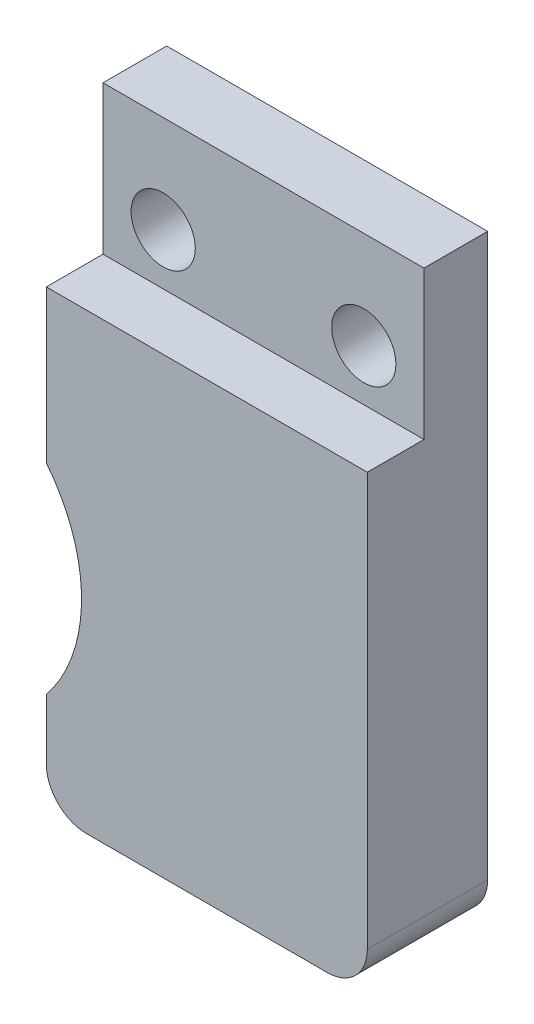
SolidWorks part; units mm, degrees
ref_plane "Front Plane" through (0, 0, 0) normal (0, 0, 1) x (1, 0, 0)
ref_plane "Top Plane" through (0, 0, 0) normal (0, 1, 0) x (1, 0, 0)
ref_plane "Right Plane" through (0, 0, 0) normal (1, 0, 0) x (0, 0, -1)
sketch "Sketch1" plane through (0, 0, 0) normal (0, 0, 1) x (1, 0, 0)
  line L0 (0, -20) -> (0, -50) construction
  line L1 (-8, -50) -> (8, -50)
  line L2 (-8, -50) -> (-8, -20)
  line L3 (-8, -20) -> (8, -20)
  line L4 (8, -50) -> (8, -20)
  line L5 (-8, -50) -> (8, -20) construction
  line L6 (-8, -20) -> (8, -50) construction
  circle A0 centre (5, -24.85) radius 1.6
  circle A2 centre (-5, -24.85) radius 1.6
  dimension "D3" = 3.2
  dimension "D7" = 5
  dimension "D8" = 4.85
  dimension "D6" = 3.2
  dimension "D1" = 30
  dimension "D2" = 16
  dimension "D4" = 5
  dimension "D5" = 4.85
extrude "Boss-Extrude1" add sketch "Sketch1" along normal blind 3.175
sketch "Sketch3" plane through (0, 0, 0) normal (0, 0, -1) x (-1, 0, 0)
  line L0 (8, -20) -> (8, -50) construction
  line L1 (-8, -50) -> (8, -50)
  line L2 (-8, -50) -> (-8, -27.4)
  line L3 (-8, -27.4) -> (8, -27.4)
  line L4 (8, -50) -> (8, -27.4)
  line L5 (-8, -20) -> (8, -20) construction
  dimension "D1" = 7.4
extrude "Boss-Extrude2" add sketch "Sketch3" against normal blind 6
fillet "Fillet1" radius 2 2 edges at (8, -50, 3) (-8, -50, 3)
sketch "Sketch4" plane through (0, 0, 3.175) normal (0, 0, 1) x (1, 0, 0)
  line L0 (-8, -20) -> (-8, -27.4) construction
  line L1 (-6, -50) -> (6, -50) construction
  line L2 (-8, -45) -> (-8, -35)
  arc A0 (-8, -45) -> (-8, -35) centre (-14.245, -40) ccw
  dimension "D2" = 8
  dimension "D1" = 5
  dimension "D3" = 10
extrude "Cut-Extrude1" cut sketch "Sketch4" against normal through all and the other way through all
